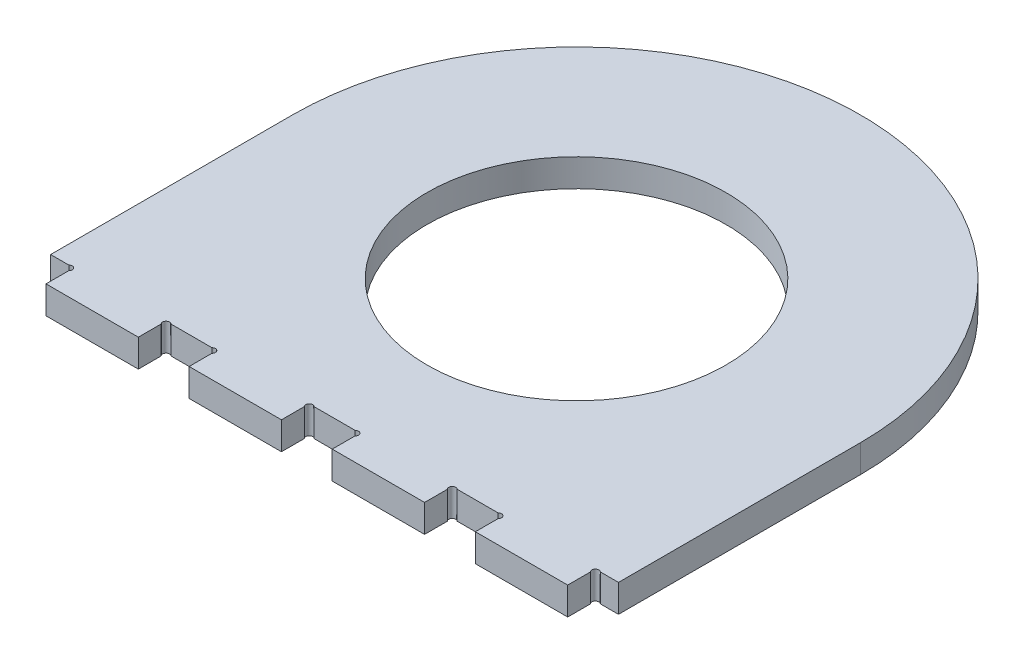
SolidWorks part; units mm, degrees
ref_plane "Alzado" through (0, 0, 0) normal (0, 0, 1) x (1, 0, 0)
ref_plane "Planta" through (0, 0, 0) normal (0, 1, 0) x (1, 0, 0)
ref_plane "Vista lateral" through (0, 0, 0) normal (1, 0, 0) x (0, 0, -1)
sketch "Croquis1" plane through (0, 0, 0) normal (0, 1, 0) x (1, 0, 0)
  line L0 (57, 0) -> (57, 104.8203)
  line L1 (295.1213, 0) -> (303, 0)
  line L2 (303, 0) -> (303, 104.8203)
  line L6 (67, -2.1213) -> (67, -12)
  line L7 (67, -12) -> (107, -12)
  line L8 (107, -12) -> (107, -2.1213)
  line L9 (129, -2.1213) -> (129, -12)
  line L10 (129, -12) -> (169, -12)
  line L11 (169, -12) -> (169, -2.1213)
  line L12 (191, -2.1213) -> (191, -12)
  line L13 (191, -12) -> (231, -12)
  line L14 (231, -12) -> (231, -2.1213)
  line L15 (253, -2.1213) -> (253, -12)
  line L16 (253, -12) -> (293, -12)
  line L17 (293, -12) -> (293, -2.1213)
  line L21 (57, 0) -> (64.8787, 0)
  line L22 (109.1213, 0) -> (126.8787, 0)
  line L23 (171.1213, 0) -> (188.8787, 0)
  line L24 (233.1213, 0) -> (250.8787, 0)
  circle A0 centre (180, 104.8203) radius 64.75
  arc A1 (303, 104.8203) -> (57, 104.8203) centre (180, 104.8203) ccw
  arc A2 (109.1213, 0) -> (107, -2.1213) centre (108.0607, -1.0607) ccw
  arc A3 (129, -2.1213) -> (126.8787, 0) centre (127.9393, -1.0607) ccw
  arc A4 (67, -2.1213) -> (64.8787, 0) centre (65.9393, -1.0607) ccw
  arc A5 (171.1213, 0) -> (169, -2.1213) centre (170.0607, -1.0607) ccw
  arc A6 (191, -2.1213) -> (188.8787, 0) centre (189.9393, -1.0607) ccw
  arc A7 (233.1213, 0) -> (231, -2.1213) centre (232.0607, -1.0607) ccw
  arc A8 (253, -2.1213) -> (250.8787, 0) centre (251.9393, -1.0607) ccw
  arc A9 (295.1213, 0) -> (293, -2.1213) centre (294.0607, -1.0607) ccw
extrude "Saliente-Extruir2" add sketch "Croquis1" along normal blind 12
